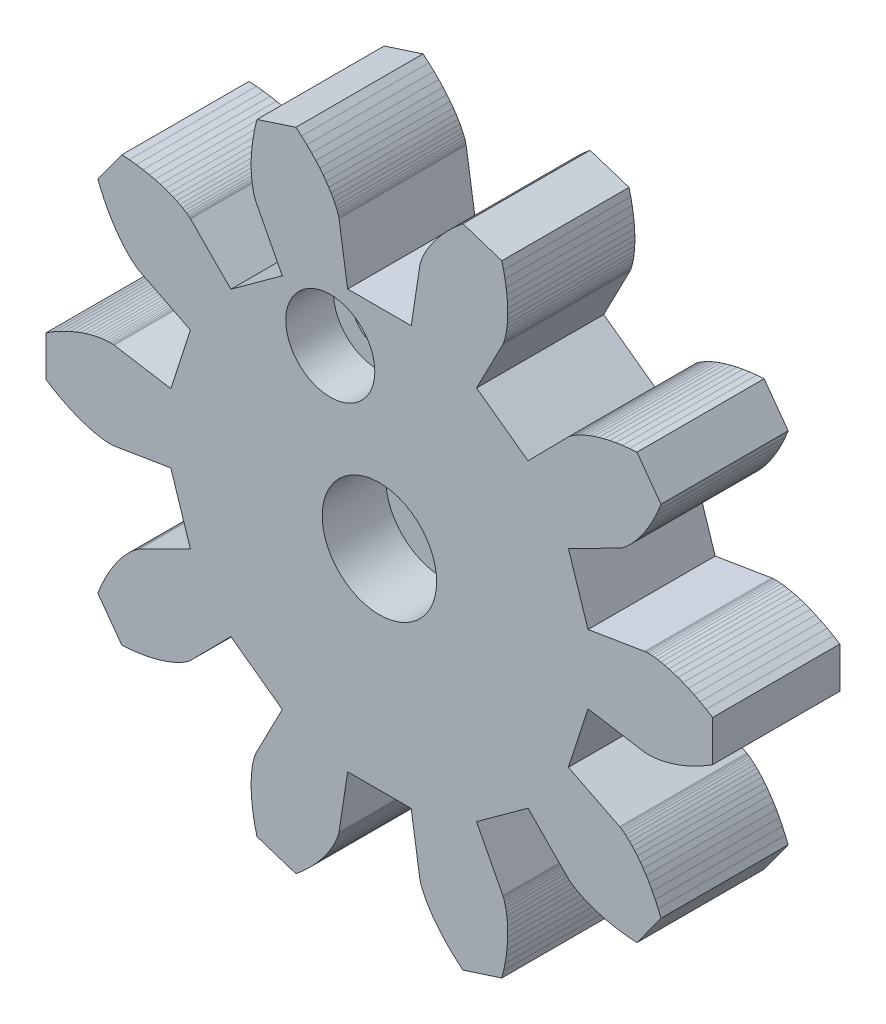
SolidWorks part; units mm, degrees
material "Acrylic (Medium-high impact)"
ref_plane "Front Plane" through (0, 0, 0) normal (0, 0, 1) x (1, 0, 0)
ref_plane "Top Plane" through (0, 0, 0) normal (0, 1, 0) x (1, 0, 0)
ref_plane "Right Plane" through (0, 0, 0) normal (1, 0, 0) x (0, 0, -1)
sketch "Model" plane through (0, 0, 0) normal (0, 0, 1) x (1, 0, 0)
  line L0 (13.1232, 2.1613) -> (16.679, 2.7469)
  line L1 (16.679, 2.7469) -> (16.6916, 2.7487)
  line L2 (16.6916, 2.7487) -> (16.7296, 2.7526)
  line L3 (16.7296, 2.7526) -> (16.793, 2.7567)
  line L4 (16.793, 2.7567) -> (16.8821, 2.7591)
  line L5 (16.8821, 2.7591) -> (16.9965, 2.7577)
  line L6 (16.9965, 2.7577) -> (17.1363, 2.7506)
  line L7 (17.1363, 2.7506) -> (17.301, 2.7358)
  line L8 (17.301, 2.7358) -> (17.4903, 2.7114)
  line L9 (17.4903, 2.7114) -> (17.7035, 2.6755)
  line L10 (17.7035, 2.6755) -> (17.9401, 2.6262)
  line L11 (17.9401, 2.6262) -> (18.1993, 2.5615)
  line L12 (18.1993, 2.5615) -> (18.4803, 2.4797)
  line L13 (18.4803, 2.4797) -> (18.7819, 2.3791)
  line L14 (18.7819, 2.3791) -> (19.1033, 2.2578)
  line L15 (19.1033, 2.2578) -> (19.4431, 2.1143)
  line L16 (19.4431, 2.1143) -> (19.8002, 1.947)
  line L17 (19.8002, 1.947) -> (20.1731, 1.7542)
  line L18 (20.1731, 1.7542) -> (20.5604, 1.5345)
  line L19 (20.5604, 1.5345) -> (20.9605, 1.2866)
  line L20 (20.9605, 1.2866) -> (20.9605, -1.2866)
  line L21 (20.9605, -1.2866) -> (20.5604, -1.5345)
  line L22 (20.5604, -1.5345) -> (20.1731, -1.7542)
  line L23 (20.1731, -1.7542) -> (19.8002, -1.947)
  line L24 (19.8002, -1.947) -> (19.4431, -2.1143)
  line L25 (19.4431, -2.1143) -> (19.1033, -2.2578)
  line L26 (19.1033, -2.2578) -> (18.7819, -2.3791)
  line L27 (18.7819, -2.3791) -> (18.4803, -2.4797)
  line L28 (18.4803, -2.4797) -> (18.1993, -2.5615)
  line L29 (18.1993, -2.5615) -> (17.9401, -2.6262)
  line L30 (17.9401, -2.6262) -> (17.7035, -2.6755)
  line L31 (17.7035, -2.6755) -> (17.4903, -2.7114)
  line L32 (17.4903, -2.7114) -> (17.301, -2.7358)
  line L33 (17.301, -2.7358) -> (17.1363, -2.7506)
  line L34 (17.1363, -2.7506) -> (16.9965, -2.7577)
  line L35 (16.9965, -2.7577) -> (16.8821, -2.7591)
  line L36 (16.8821, -2.7591) -> (16.793, -2.7567)
  line L37 (16.793, -2.7567) -> (16.7296, -2.7526)
  line L38 (16.7296, -2.7526) -> (16.6916, -2.7487)
  line L39 (16.6916, -2.7487) -> (16.679, -2.7469)
  line L40 (16.679, -2.7469) -> (13.1232, -2.1613)
  line L41 (13.1232, -2.1613) -> (11.8873, -5.9651)
  line L42 (11.8873, -5.9651) -> (15.1082, -7.5814)
  line L43 (15.1082, -7.5814) -> (15.1194, -7.5874)
  line L44 (15.1194, -7.5874) -> (15.1525, -7.6065)
  line L45 (15.1525, -7.6065) -> (15.2062, -7.6405)
  line L46 (15.2062, -7.6405) -> (15.2796, -7.6909)
  line L47 (15.2796, -7.6909) -> (15.3714, -7.7593)
  line L48 (15.3714, -7.7593) -> (15.4803, -7.8472)
  line L49 (15.4803, -7.8472) -> (15.6049, -7.9559)
  line L50 (15.6049, -7.9559) -> (15.7437, -8.0869)
  line L51 (15.7437, -8.0869) -> (15.8951, -8.2413)
  line L52 (15.8951, -8.2413) -> (16.0575, -8.4203)
  line L53 (16.0575, -8.4203) -> (16.2292, -8.625)
  line L54 (16.2292, -8.625) -> (16.4084, -8.8563)
  line L55 (16.4084, -8.8563) -> (16.5933, -9.115)
  line L56 (16.5933, -9.115) -> (16.782, -9.402)
  line L57 (16.782, -9.402) -> (16.9726, -9.7179)
  line L58 (16.9726, -9.7179) -> (17.1631, -10.0632)
  line L59 (17.1631, -10.0632) -> (17.3515, -10.4383)
  line L60 (17.3515, -10.4383) -> (17.5357, -10.8437)
  line L61 (17.5357, -10.8437) -> (17.7137, -11.2794)
  line L62 (17.7137, -11.2794) -> (16.2012, -13.3612)
  line L63 (16.2012, -13.3612) -> (15.7318, -13.3266)
  line L64 (15.7318, -13.3266) -> (15.2893, -13.2766)
  line L65 (15.2893, -13.2766) -> (14.8743, -13.2134)
  line L66 (14.8743, -13.2134) -> (14.4871, -13.1389)
  line L67 (14.4871, -13.1389) -> (14.1278, -13.0553)
  line L68 (14.1278, -13.0553) -> (13.7965, -12.9645)
  line L69 (13.7965, -12.9645) -> (13.4933, -12.8686)
  line L70 (13.4933, -12.8686) -> (13.218, -12.7696)
  line L71 (13.218, -12.7696) -> (12.9703, -12.6695)
  line L72 (12.9703, -12.6695) -> (12.7498, -12.5704)
  line L73 (12.7498, -12.5704) -> (12.5562, -12.4741)
  line L74 (12.5562, -12.4741) -> (12.3887, -12.3826)
  line L75 (12.3887, -12.3826) -> (12.2468, -12.2978)
  line L76 (12.2468, -12.2978) -> (12.1296, -12.2214)
  line L77 (12.1296, -12.2214) -> (12.0361, -12.1552)
  line L78 (12.0361, -12.1552) -> (11.9655, -12.1009)
  line L79 (11.9655, -12.1009) -> (11.9166, -12.0603)
  line L80 (11.9166, -12.0603) -> (11.8882, -12.0348)
  line L81 (11.8882, -12.0348) -> (11.879, -12.026)
  line L82 (11.879, -12.026) -> (9.3465, -9.4622)
  line L83 (9.3465, -9.4622) -> (6.1108, -11.813)
  line L84 (6.1108, -11.813) -> (7.7666, -15.0138)
  line L85 (7.7666, -15.0138) -> (7.7721, -15.0253)
  line L86 (7.7721, -15.0253) -> (7.7876, -15.0602)
  line L87 (7.7876, -15.0602) -> (7.8111, -15.1193)
  line L88 (7.8111, -15.1193) -> (7.8409, -15.2032)
  line L89 (7.8409, -15.2032) -> (7.875, -15.3125)
  line L90 (7.875, -15.3125) -> (7.9114, -15.4476)
  line L91 (7.9114, -15.4476) -> (7.9482, -15.6088)
  line L92 (7.9482, -15.6088) -> (7.9835, -15.7963)
  line L93 (7.9835, -15.7963) -> (8.0153, -16.0103)
  line L94 (8.0153, -16.0103) -> (8.0414, -16.2505)
  line L95 (8.0414, -16.2505) -> (8.06, -16.517)
  line L96 (8.06, -16.517) -> (8.0691, -16.8095)
  line L97 (8.0691, -16.8095) -> (8.0666, -17.1275)
  line L98 (8.0666, -17.1275) -> (8.0506, -17.4706)
  line L99 (8.0506, -17.4706) -> (8.0191, -17.8382)
  line L100 (8.0191, -17.8382) -> (7.9703, -18.2295)
  line L101 (7.9703, -18.2295) -> (7.9022, -18.6437)
  line L102 (7.9022, -18.6437) -> (7.8129, -19.0799)
  line L103 (7.8129, -19.0799) -> (7.7008, -19.5371)
  line L104 (7.7008, -19.5371) -> (5.2535, -20.3322)
  line L105 (5.2535, -20.3322) -> (4.8941, -20.0283)
  line L106 (4.8941, -20.0283) -> (4.5655, -19.7279)
  line L107 (4.5655, -19.7279) -> (4.2669, -19.4328)
  line L108 (4.2669, -19.4328) -> (3.9974, -19.1449)
  line L109 (3.9974, -19.1449) -> (3.7559, -18.866)
  line L110 (3.7559, -18.866) -> (3.5413, -18.5979)
  line L111 (3.5413, -18.5979) -> (3.3523, -18.342)
  line L112 (3.3523, -18.342) -> (3.1878, -18.1001)
  line L113 (3.1878, -18.1001) -> (3.0462, -17.8736)
  line L114 (3.0462, -17.8736) -> (2.9261, -17.6638)
  line L115 (2.9261, -17.6638) -> (2.826, -17.4721)
  line L116 (2.826, -17.4721) -> (2.7444, -17.2997)
  line L117 (2.7444, -17.2997) -> (2.6794, -17.1476)
  line L118 (2.6794, -17.1476) -> (2.6295, -17.0169)
  line L119 (2.6295, -17.0169) -> (2.5928, -16.9084)
  line L120 (2.5928, -16.9084) -> (2.5675, -16.823)
  line L121 (2.5675, -16.823) -> (2.5518, -16.7614)
  line L122 (2.5518, -16.7614) -> (2.5438, -16.7241)
  line L123 (2.5438, -16.7241) -> (2.5416, -16.7115)
  line L124 (2.5416, -16.7115) -> (1.9998, -13.1488)
  line L125 (1.9998, -13.1488) -> (-1.9998, -13.1488)
  line L126 (-1.9998, -13.1488) -> (-2.5416, -16.7115)
  line L127 (-2.5416, -16.7115) -> (-2.5438, -16.7241)
  line L128 (-2.5438, -16.7241) -> (-2.5518, -16.7614)
  line L129 (-2.5518, -16.7614) -> (-2.5675, -16.823)
  line L130 (-2.5675, -16.823) -> (-2.5928, -16.9084)
  line L131 (-2.5928, -16.9084) -> (-2.6295, -17.0169)
  line L132 (-2.6295, -17.0169) -> (-2.6794, -17.1476)
  line L133 (-2.6794, -17.1476) -> (-2.7444, -17.2997)
  line L134 (-2.7444, -17.2997) -> (-2.826, -17.4721)
  line L135 (-2.826, -17.4721) -> (-2.9261, -17.6638)
  line L136 (-2.9261, -17.6638) -> (-3.0462, -17.8736)
  line L137 (-3.0462, -17.8736) -> (-3.1878, -18.1001)
  line L138 (-3.1878, -18.1001) -> (-3.3523, -18.342)
  line L139 (-3.3523, -18.342) -> (-3.5413, -18.5979)
  line L140 (-3.5413, -18.5979) -> (-3.7559, -18.866)
  line L141 (-3.7559, -18.866) -> (-3.9974, -19.1449)
  line L142 (-3.9974, -19.1449) -> (-4.2669, -19.4328)
  line L143 (-4.2669, -19.4328) -> (-4.5655, -19.7279)
  line L144 (-4.5655, -19.7279) -> (-4.8941, -20.0283)
  line L145 (-4.8941, -20.0283) -> (-5.2535, -20.3322)
  line L146 (-5.2535, -20.3322) -> (-7.7008, -19.5371)
  line L147 (-7.7008, -19.5371) -> (-7.8129, -19.0799)
  line L148 (-7.8129, -19.0799) -> (-7.9022, -18.6437)
  line L149 (-7.9022, -18.6437) -> (-7.9703, -18.2295)
  line L150 (-7.9703, -18.2295) -> (-8.0191, -17.8382)
  line L151 (-8.0191, -17.8382) -> (-8.0506, -17.4706)
  line L152 (-8.0506, -17.4706) -> (-8.0666, -17.1275)
  line L153 (-8.0666, -17.1275) -> (-8.0691, -16.8095)
  line L154 (-8.0691, -16.8095) -> (-8.06, -16.517)
  line L155 (-8.06, -16.517) -> (-8.0414, -16.2505)
  line L156 (-8.0414, -16.2505) -> (-8.0153, -16.0103)
  line L157 (-8.0153, -16.0103) -> (-7.9835, -15.7963)
  line L158 (-7.9835, -15.7963) -> (-7.9482, -15.6088)
  line L159 (-7.9482, -15.6088) -> (-7.9114, -15.4476)
  line L160 (-7.9114, -15.4476) -> (-7.875, -15.3125)
  line L161 (-7.875, -15.3125) -> (-7.8409, -15.2032)
  line L162 (-7.8409, -15.2032) -> (-7.8111, -15.1193)
  line L163 (-7.8111, -15.1193) -> (-7.7876, -15.0602)
  line L164 (-7.7876, -15.0602) -> (-7.7721, -15.0253)
  line L165 (-7.7721, -15.0253) -> (-7.7666, -15.0138)
  line L166 (-7.7666, -15.0138) -> (-6.1108, -11.813)
  line L167 (-6.1108, -11.813) -> (-9.3465, -9.4622)
  line L168 (-9.3465, -9.4622) -> (-11.879, -12.026)
  line L169 (-11.879, -12.026) -> (-11.8882, -12.0348)
  line L170 (-11.8882, -12.0348) -> (-11.9166, -12.0603)
  line L171 (-11.9166, -12.0603) -> (-11.9655, -12.1009)
  line L172 (-11.9655, -12.1009) -> (-12.0361, -12.1552)
  line L173 (-12.0361, -12.1552) -> (-12.1296, -12.2214)
  line L174 (-12.1296, -12.2214) -> (-12.2468, -12.2978)
  line L175 (-12.2468, -12.2978) -> (-12.3887, -12.3826)
  line L176 (-12.3887, -12.3826) -> (-12.5562, -12.4741)
  line L177 (-12.5562, -12.4741) -> (-12.7498, -12.5704)
  line L178 (-12.7498, -12.5704) -> (-12.9703, -12.6695)
  line L179 (-12.9703, -12.6695) -> (-13.218, -12.7696)
  line L180 (-13.218, -12.7696) -> (-13.4933, -12.8686)
  line L181 (-13.4933, -12.8686) -> (-13.7965, -12.9645)
  line L182 (-13.7965, -12.9645) -> (-14.1278, -13.0553)
  line L183 (-14.1278, -13.0553) -> (-14.4871, -13.1389)
  line L184 (-14.4871, -13.1389) -> (-14.8743, -13.2134)
  line L185 (-14.8743, -13.2134) -> (-15.2893, -13.2766)
  line L186 (-15.2893, -13.2766) -> (-15.7318, -13.3266)
  line L187 (-15.7318, -13.3266) -> (-16.2012, -13.3612)
  line L188 (-16.2012, -13.3612) -> (-17.7137, -11.2794)
  line L189 (-17.7137, -11.2794) -> (-17.5357, -10.8437)
  line L190 (-17.5357, -10.8437) -> (-17.3515, -10.4383)
  line L191 (-17.3515, -10.4383) -> (-17.1631, -10.0632)
  line L192 (-17.1631, -10.0632) -> (-16.9726, -9.7179)
  line L193 (-16.9726, -9.7179) -> (-16.782, -9.402)
  line L194 (-16.782, -9.402) -> (-16.5933, -9.115)
  line L195 (-16.5933, -9.115) -> (-16.4084, -8.8563)
  line L196 (-16.4084, -8.8563) -> (-16.2292, -8.625)
  line L197 (-16.2292, -8.625) -> (-16.0575, -8.4203)
  line L198 (-16.0575, -8.4203) -> (-15.8951, -8.2413)
  line L199 (-15.8951, -8.2413) -> (-15.7437, -8.0869)
  line L200 (-15.7437, -8.0869) -> (-15.6049, -7.9559)
  line L201 (-15.6049, -7.9559) -> (-15.4803, -7.8472)
  line L202 (-15.4803, -7.8472) -> (-15.3714, -7.7593)
  line L203 (-15.3714, -7.7593) -> (-15.2796, -7.6909)
  line L204 (-15.2796, -7.6909) -> (-15.2062, -7.6405)
  line L205 (-15.2062, -7.6405) -> (-15.1525, -7.6065)
  line L206 (-15.1525, -7.6065) -> (-15.1194, -7.5874)
  line L207 (-15.1194, -7.5874) -> (-15.1082, -7.5814)
  line L208 (-15.1082, -7.5814) -> (-11.8873, -5.9651)
  line L209 (-11.8873, -5.9651) -> (-13.1232, -2.1613)
  line L210 (-13.1232, -2.1613) -> (-16.679, -2.7469)
  line L211 (-16.679, -2.7469) -> (-16.6916, -2.7487)
  line L212 (-16.6916, -2.7487) -> (-16.7296, -2.7526)
  line L213 (-16.7296, -2.7526) -> (-16.793, -2.7567)
  line L214 (-16.793, -2.7567) -> (-16.8821, -2.7591)
  line L215 (-16.8821, -2.7591) -> (-16.9965, -2.7577)
  line L216 (-16.9965, -2.7577) -> (-17.1363, -2.7506)
  line L217 (-17.1363, -2.7506) -> (-17.301, -2.7358)
  line L218 (-17.301, -2.7358) -> (-17.4903, -2.7114)
  line L219 (-17.4903, -2.7114) -> (-17.7035, -2.6755)
  line L220 (-17.7035, -2.6755) -> (-17.9401, -2.6262)
  line L221 (-17.9401, -2.6262) -> (-18.1993, -2.5615)
  line L222 (-18.1993, -2.5615) -> (-18.4803, -2.4797)
  line L223 (-18.4803, -2.4797) -> (-18.7819, -2.3791)
  line L224 (-18.7819, -2.3791) -> (-19.1033, -2.2578)
  line L225 (-19.1033, -2.2578) -> (-19.4431, -2.1143)
  line L226 (-19.4431, -2.1143) -> (-19.8002, -1.947)
  line L227 (-19.8002, -1.947) -> (-20.1731, -1.7542)
  line L228 (-20.1731, -1.7542) -> (-20.5604, -1.5345)
  line L229 (-20.5604, -1.5345) -> (-20.9605, -1.2866)
  line L230 (-20.9605, -1.2866) -> (-20.9605, 1.2866)
  line L231 (-20.9605, 1.2866) -> (-20.5604, 1.5345)
  line L232 (-20.5604, 1.5345) -> (-20.1731, 1.7542)
  line L233 (-20.1731, 1.7542) -> (-19.8002, 1.947)
  line L234 (-19.8002, 1.947) -> (-19.4431, 2.1143)
  line L235 (-19.4431, 2.1143) -> (-19.1033, 2.2578)
  line L236 (-19.1033, 2.2578) -> (-18.7819, 2.3791)
  line L237 (-18.7819, 2.3791) -> (-18.4803, 2.4797)
  line L238 (-18.4803, 2.4797) -> (-18.1993, 2.5615)
  line L239 (-18.1993, 2.5615) -> (-17.9401, 2.6262)
  line L240 (-17.9401, 2.6262) -> (-17.7035, 2.6755)
  line L241 (-17.7035, 2.6755) -> (-17.4903, 2.7114)
  line L242 (-17.4903, 2.7114) -> (-17.301, 2.7358)
  line L243 (-17.301, 2.7358) -> (-17.1363, 2.7506)
  line L244 (-17.1363, 2.7506) -> (-16.9965, 2.7577)
  line L245 (-16.9965, 2.7577) -> (-16.8821, 2.7591)
  line L246 (-16.8821, 2.7591) -> (-16.793, 2.7567)
  line L247 (-16.793, 2.7567) -> (-16.7296, 2.7526)
  line L248 (-16.7296, 2.7526) -> (-16.6916, 2.7487)
  line L249 (-16.6916, 2.7487) -> (-16.679, 2.7469)
  line L250 (-16.679, 2.7469) -> (-13.1232, 2.1613)
  line L251 (-13.1232, 2.1613) -> (-11.8873, 5.9651)
  line L252 (-11.8873, 5.9651) -> (-15.1082, 7.5814)
  line L253 (-15.1082, 7.5814) -> (-15.1194, 7.5874)
  line L254 (-15.1194, 7.5874) -> (-15.1525, 7.6065)
  line L255 (-15.1525, 7.6065) -> (-15.2062, 7.6405)
  line L256 (-15.2062, 7.6405) -> (-15.2796, 7.6909)
  line L257 (-15.2796, 7.6909) -> (-15.3714, 7.7593)
  line L258 (-15.3714, 7.7593) -> (-15.4803, 7.8472)
  line L259 (-15.4803, 7.8472) -> (-15.6049, 7.9559)
  line L260 (-15.6049, 7.9559) -> (-15.7437, 8.0869)
  line L261 (-15.7437, 8.0869) -> (-15.8951, 8.2413)
  line L262 (-15.8951, 8.2413) -> (-16.0575, 8.4203)
  line L263 (-16.0575, 8.4203) -> (-16.2292, 8.625)
  line L264 (-16.2292, 8.625) -> (-16.4084, 8.8563)
  line L265 (-16.4084, 8.8563) -> (-16.5933, 9.115)
  line L266 (-16.5933, 9.115) -> (-16.782, 9.402)
  line L267 (-16.782, 9.402) -> (-16.9726, 9.7179)
  line L268 (-16.9726, 9.7179) -> (-17.1631, 10.0632)
  line L269 (-17.1631, 10.0632) -> (-17.3515, 10.4383)
  line L270 (-17.3515, 10.4383) -> (-17.5357, 10.8437)
  line L271 (-17.5357, 10.8437) -> (-17.7137, 11.2794)
  line L272 (-17.7137, 11.2794) -> (-16.2012, 13.3612)
  line L273 (-16.2012, 13.3612) -> (-15.7318, 13.3266)
  line L274 (-15.7318, 13.3266) -> (-15.2893, 13.2766)
  line L275 (-15.2893, 13.2766) -> (-14.8743, 13.2134)
  line L276 (-14.8743, 13.2134) -> (-14.4871, 13.1389)
  line L277 (-14.4871, 13.1389) -> (-14.1278, 13.0553)
  line L278 (-14.1278, 13.0553) -> (-13.7965, 12.9645)
  line L279 (-13.7965, 12.9645) -> (-13.4933, 12.8686)
  line L280 (-13.4933, 12.8686) -> (-13.218, 12.7696)
  line L281 (-13.218, 12.7696) -> (-12.9703, 12.6695)
  line L282 (-12.9703, 12.6695) -> (-12.7498, 12.5704)
  line L283 (-12.7498, 12.5704) -> (-12.5562, 12.4741)
  line L284 (-12.5562, 12.4741) -> (-12.3887, 12.3826)
  line L285 (-12.3887, 12.3826) -> (-12.2468, 12.2978)
  line L286 (-12.2468, 12.2978) -> (-12.1296, 12.2214)
  line L287 (-12.1296, 12.2214) -> (-12.0361, 12.1552)
  line L288 (-12.0361, 12.1552) -> (-11.9655, 12.1009)
  line L289 (-11.9655, 12.1009) -> (-11.9166, 12.0603)
  line L290 (-11.9166, 12.0603) -> (-11.8882, 12.0348)
  line L291 (-11.8882, 12.0348) -> (-11.879, 12.026)
  line L292 (-11.879, 12.026) -> (-9.3465, 9.4622)
  line L293 (-9.3465, 9.4622) -> (-6.1108, 11.813)
  line L294 (-6.1108, 11.813) -> (-7.7666, 15.0138)
  line L295 (-7.7666, 15.0138) -> (-7.7721, 15.0253)
  line L296 (-7.7721, 15.0253) -> (-7.7876, 15.0602)
  line L297 (-7.7876, 15.0602) -> (-7.8111, 15.1193)
  line L298 (-7.8111, 15.1193) -> (-7.8409, 15.2032)
  line L299 (-7.8409, 15.2032) -> (-7.875, 15.3125)
  line L300 (-7.875, 15.3125) -> (-7.9114, 15.4476)
  line L301 (-7.9114, 15.4476) -> (-7.9482, 15.6088)
  line L302 (-7.9482, 15.6088) -> (-7.9835, 15.7963)
  line L303 (-7.9835, 15.7963) -> (-8.0153, 16.0103)
  line L304 (-8.0153, 16.0103) -> (-8.0414, 16.2505)
  line L305 (-8.0414, 16.2505) -> (-8.06, 16.517)
  line L306 (-8.06, 16.517) -> (-8.0691, 16.8095)
  line L307 (-8.0691, 16.8095) -> (-8.0666, 17.1275)
  line L308 (-8.0666, 17.1275) -> (-8.0506, 17.4706)
  line L309 (-8.0506, 17.4706) -> (-8.0191, 17.8382)
  line L310 (-8.0191, 17.8382) -> (-7.9703, 18.2295)
  line L311 (-7.9703, 18.2295) -> (-7.9022, 18.6437)
  line L312 (-7.9022, 18.6437) -> (-7.8129, 19.0799)
  line L313 (-7.8129, 19.0799) -> (-7.7008, 19.5371)
  line L314 (-7.7008, 19.5371) -> (-5.2535, 20.3322)
  line L315 (-5.2535, 20.3322) -> (-4.8941, 20.0283)
  line L316 (-4.8941, 20.0283) -> (-4.5655, 19.7279)
  line L317 (-4.5655, 19.7279) -> (-4.2669, 19.4328)
  line L318 (-4.2669, 19.4328) -> (-3.9974, 19.1449)
  line L319 (-3.9974, 19.1449) -> (-3.7559, 18.866)
  line L320 (-3.7559, 18.866) -> (-3.5413, 18.5979)
  line L321 (-3.5413, 18.5979) -> (-3.3523, 18.342)
  line L322 (-3.3523, 18.342) -> (-3.1878, 18.1001)
  line L323 (-3.1878, 18.1001) -> (-3.0462, 17.8736)
  line L324 (-3.0462, 17.8736) -> (-2.9261, 17.6638)
  line L325 (-2.9261, 17.6638) -> (-2.826, 17.4721)
  line L326 (-2.826, 17.4721) -> (-2.7444, 17.2997)
  line L327 (-2.7444, 17.2997) -> (-2.6794, 17.1476)
  line L328 (-2.6794, 17.1476) -> (-2.6295, 17.0169)
  line L329 (-2.6295, 17.0169) -> (-2.5928, 16.9084)
  line L330 (-2.5928, 16.9084) -> (-2.5675, 16.823)
  line L331 (-2.5675, 16.823) -> (-2.5518, 16.7614)
  line L332 (-2.5518, 16.7614) -> (-2.5438, 16.7241)
  line L333 (-2.5438, 16.7241) -> (-2.5416, 16.7115)
  line L334 (-2.5416, 16.7115) -> (-1.9998, 13.1488)
  line L335 (-1.9998, 13.1488) -> (1.9998, 13.1488)
  line L336 (1.9998, 13.1488) -> (2.5416, 16.7115)
  line L337 (2.5416, 16.7115) -> (2.5438, 16.7241)
  line L338 (2.5438, 16.7241) -> (2.5518, 16.7614)
  line L339 (2.5518, 16.7614) -> (2.5675, 16.823)
  line L340 (2.5675, 16.823) -> (2.5928, 16.9084)
  line L341 (2.5928, 16.9084) -> (2.6295, 17.0169)
  line L342 (2.6295, 17.0169) -> (2.6794, 17.1476)
  line L343 (2.6794, 17.1476) -> (2.7444, 17.2997)
  line L344 (2.7444, 17.2997) -> (2.826, 17.4721)
  line L345 (2.826, 17.4721) -> (2.9261, 17.6638)
  line L346 (2.9261, 17.6638) -> (3.0462, 17.8736)
  line L347 (3.0462, 17.8736) -> (3.1878, 18.1001)
  line L348 (3.1878, 18.1001) -> (3.3523, 18.342)
  line L349 (3.3523, 18.342) -> (3.5413, 18.5979)
  line L350 (3.5413, 18.5979) -> (3.7559, 18.866)
  line L351 (3.7559, 18.866) -> (3.9974, 19.1449)
  line L352 (3.9974, 19.1449) -> (4.2669, 19.4328)
  line L353 (4.2669, 19.4328) -> (4.5655, 19.7279)
  line L354 (4.5655, 19.7279) -> (4.8941, 20.0283)
  line L355 (4.8941, 20.0283) -> (5.2535, 20.3322)
  line L356 (5.2535, 20.3322) -> (7.7008, 19.5371)
  line L357 (7.7008, 19.5371) -> (7.8129, 19.0799)
  line L358 (7.8129, 19.0799) -> (7.9022, 18.6437)
  line L359 (7.9022, 18.6437) -> (7.9703, 18.2295)
  line L360 (7.9703, 18.2295) -> (8.0191, 17.8382)
  line L361 (8.0191, 17.8382) -> (8.0506, 17.4706)
  line L362 (8.0506, 17.4706) -> (8.0666, 17.1275)
  line L363 (8.0666, 17.1275) -> (8.0691, 16.8095)
  line L364 (8.0691, 16.8095) -> (8.06, 16.517)
  line L365 (8.06, 16.517) -> (8.0414, 16.2505)
  line L366 (8.0414, 16.2505) -> (8.0153, 16.0103)
  line L367 (8.0153, 16.0103) -> (7.9835, 15.7963)
  line L368 (7.9835, 15.7963) -> (7.9482, 15.6088)
  line L369 (7.9482, 15.6088) -> (7.9114, 15.4476)
  line L370 (7.9114, 15.4476) -> (7.875, 15.3125)
  line L371 (7.875, 15.3125) -> (7.8409, 15.2032)
  line L372 (7.8409, 15.2032) -> (7.8111, 15.1193)
  line L373 (7.8111, 15.1193) -> (7.7876, 15.0602)
  line L374 (7.7876, 15.0602) -> (7.7721, 15.0253)
  line L375 (7.7721, 15.0253) -> (7.7666, 15.0138)
  line L376 (7.7666, 15.0138) -> (6.1108, 11.813)
  line L377 (6.1108, 11.813) -> (9.3465, 9.4622)
  line L378 (9.3465, 9.4622) -> (11.879, 12.026)
  line L379 (11.879, 12.026) -> (11.8882, 12.0348)
  line L380 (11.8882, 12.0348) -> (11.9166, 12.0603)
  line L381 (11.9166, 12.0603) -> (11.9655, 12.1009)
  line L382 (11.9655, 12.1009) -> (12.0361, 12.1552)
  line L383 (12.0361, 12.1552) -> (12.1296, 12.2214)
  line L384 (12.1296, 12.2214) -> (12.2468, 12.2978)
  line L385 (12.2468, 12.2978) -> (12.3887, 12.3826)
  line L386 (12.3887, 12.3826) -> (12.5562, 12.4741)
  line L387 (12.5562, 12.4741) -> (12.7498, 12.5704)
  line L388 (12.7498, 12.5704) -> (12.9703, 12.6695)
  line L389 (12.9703, 12.6695) -> (13.218, 12.7696)
  line L390 (13.218, 12.7696) -> (13.4933, 12.8686)
  line L391 (13.4933, 12.8686) -> (13.7965, 12.9645)
  line L392 (13.7965, 12.9645) -> (14.1278, 13.0553)
  line L393 (14.1278, 13.0553) -> (14.4871, 13.1389)
  line L394 (14.4871, 13.1389) -> (14.8743, 13.2134)
  line L395 (14.8743, 13.2134) -> (15.2893, 13.2766)
  line L396 (15.2893, 13.2766) -> (15.7318, 13.3266)
  line L397 (15.7318, 13.3266) -> (16.2012, 13.3612)
  line L398 (16.2012, 13.3612) -> (17.7137, 11.2794)
  line L399 (17.7137, 11.2794) -> (17.5357, 10.8437)
  line L400 (17.5357, 10.8437) -> (17.3515, 10.4383)
  line L401 (17.3515, 10.4383) -> (17.1631, 10.0632)
  line L402 (17.1631, 10.0632) -> (16.9726, 9.7179)
  line L403 (16.9726, 9.7179) -> (16.782, 9.402)
  line L404 (16.782, 9.402) -> (16.5933, 9.115)
  line L405 (16.5933, 9.115) -> (16.4084, 8.8563)
  line L406 (16.4084, 8.8563) -> (16.2292, 8.625)
  line L407 (16.2292, 8.625) -> (16.0575, 8.4203)
  line L408 (16.0575, 8.4203) -> (15.8951, 8.2413)
  line L409 (15.8951, 8.2413) -> (15.7437, 8.0869)
  line L410 (15.7437, 8.0869) -> (15.6049, 7.9559)
  line L411 (15.6049, 7.9559) -> (15.4803, 7.8472)
  line L412 (15.4803, 7.8472) -> (15.3714, 7.7593)
  line L413 (15.3714, 7.7593) -> (15.2796, 7.6909)
  line L414 (15.2796, 7.6909) -> (15.2062, 7.6405)
  line L415 (15.2062, 7.6405) -> (15.1525, 7.6065)
  line L416 (15.1525, 7.6065) -> (15.1194, 7.5874)
  line L417 (15.1194, 7.5874) -> (15.1082, 7.5814)
  line L418 (15.1082, 7.5814) -> (11.8873, 5.9651)
  line L419 (11.8873, 5.9651) -> (13.1232, 2.1613)
extrude "Boss-Extrude1" add sketch "Model" along normal blind 8 contours L210 L211 L212 L213 L214 L215 L216 L217 L218 L219 L220 L221 L222 L223 L224 L225 L226 L227 L228 L229 L230 L231 L232 L233 L234 L235 L236 L237 L238 L239 L240 L241 L242 L243 L244 L245 L246 L247 L248 L249 L250 L251 L252 L253 L254 L255 L256 L257 L258 L259 L260 L261 L262 L263 L264 L265 L266 L267 L268 L269 L270 L271 L272 L273 L274 L275 L276 L277 L278 L279 L280 L281 L282 L283 L284 L285 L286 L287 L288 L289 L290 L291 L292 L293 L294 L295 L296 L297 L298 L299 L300 L301 L302 L303 L304 L305 L306 L307 L308 L309 L310 L311 L312 L313 L314 L315 L316 L317 L318 L319 L320 L321 L322 L323 L324 L325 L326 L327 L328 L329 L330 L331 L332 L333 L334 L335 L336 L337 L338 L339 L340 L341 L342 L343 L344 L345 L346 L347 L348 L349 L350 L351 L352 L353 L354 L355 L356 L357 L358 L359 L360 L361 L362 L363 L364 L365 L366 L367 L368 L369 L370 L371 L372 L373 L374 L375 L376 L377 L378 L379 L380 L381 L382 L383 L384 L385 L386 L387 L388 L389 L390 L391 L392 L393 L394 L395 L396 L397 L398 L399 L400 L401 L402 L403 L404 L405 L406 L407 L408 L409 L410 L411 L412 L413 L414 L415 L416 L417 L418 L419 L0 L1 L2 L3 L4 L5 L6 L7 L8 L9 L10 L11 L12 L13 L14 L15 L16 L17 L18 L19 L20 L21 L22 L23 L24 L25 L26 L27 L28 L29 L30 L31 L32 L33 L34 L35 L36 L37 L38 L39 L40 L41 L42 L43 L44 L45 L46 L47 L48 L49 L50 L51 L52 L53 L54 L55 L56 L57 L58 L59 L60 L61 L62 L63 L64 L65 L66 L67 L68 L69 L70 L71 L72 L73 L74 L75 L76 L77 L78 L79 L80 L81 L82 L83 L84 L85 L86 L87 L88 L89 L90 L91 L92 L93 L94 L95 L96 L97 L98 L99 L100 L101 L102 L103 L104 L105 L106 L107 L108 L109 L110 L111 L112 L113 L114 L115 L116 L117 L118 L119 L120 L121 L122 L123 L124 L125 L126 L127 L128 L129 L130 L131 L132 L133 L134 L135 L136 L137 L138 L139 L140 L141 L142 L143 L144 L145 L146 L147 L148 L149 L150 L151 L152 L153 L154 L155 L156 L157 L158 L159 L160 L161 L162 L163 L164 L165 L166 L167 L168 L169 L170 L171 L172 L173 L174 L175 L176 L177 L178 L179 L180 L181 L182 L183 L184 L185 L186 L187 L188 L189 L190 L191 L192 L193 L194 L195 L196 L197 L198 L199 L200 L201 L202 L203 L204 L205 L206 L207 L208 L209
sketch "Sketch2" plane through (0, 0, 8) normal (0, 0, 1) x (1, 0, 0)
  circle A0 centre (0, 0) radius 3.6
  dimension "D1" = 7.2
extrude "Cut-Extrude1" cut sketch "Sketch2" against normal blind 4
sketch "Sketch3" plane through (0, 0, 8) normal (0, 0, 1) x (1, 0, 0)
  line L0 (-6.1108, 11.813) -> (-1.9998, 13.1488) construction
  line L1 (-4.0553, 12.4809) -> (0, 0) construction
  circle A0 centre (-3.0902, 9.5106) radius 1.6
  dimension "D1" = 3.2
  dimension "D2" = 10
extrude "Cut-Extrude2" cut sketch "Sketch3" against normal through all
sketch "Sketch4" plane through (0, 0, 8) normal (0, 0, 1) x (1, 0, 0)
  circle A0 centre (0, 0) radius 17.5 construction
  dimension "D1" = 35
sketch "Sketch7" plane through (0, 0, 8) normal (0, 0, 1) x (1, 0, 0)
  circle A0 centre (-3.0902, 9.5106) radius 2.8
  dimension "D1" = 5.6
extrude "Cut-Extrude3" cut sketch "Sketch7" against normal blind 3
sketch "Sketch8" plane through (0, 0, 0) normal (0, 0, -1) x (-1, 0, 0)
  circle A0 centre (0, 0) radius 1.55
  dimension "D1" = 3.1
extrude "Cut-Extrude4" cut sketch "Sketch8" against normal blind 3
